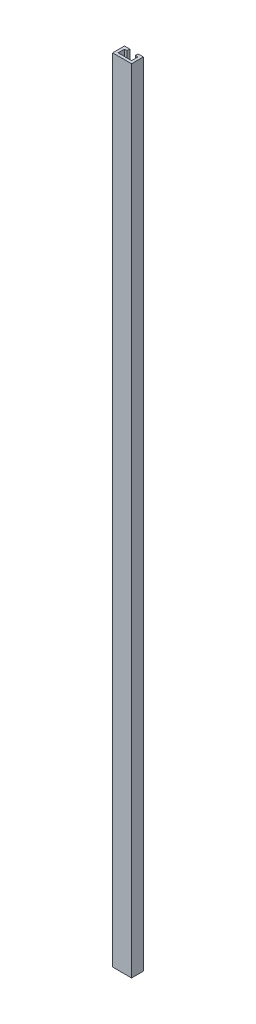
SolidWorks part; units mm, degrees
ref_plane "前视基准面" through (0, 0, 0) normal (0, 0, 1) x (1, 0, 0)
ref_plane "上视基准面" through (0, 0, 0) normal (0, 1, 0) x (1, 0, 0)
ref_plane "右视基准面" through (0, 0, 0) normal (1, 0, 0) x (0, 0, -1)
sketch "草图1" plane through (0, 0, 0) normal (0, 1, 0) x (1, 0, 0)
  line L0 (0, -5) -> (8, -5)
  line L1 (8, -5) -> (8, 0)
  line L2 (8, 0) -> (5.75, 0)
  line L3 (5.75, 0) -> (5.75, -1.15)
  line L4 (5.75, -1.15) -> (6.85, -1.15)
  line L5 (6.85, -1.15) -> (6.85, -3.85)
  line L6 (6.85, -3.85) -> (1.15, -3.85)
  line L7 (1.15, -3.85) -> (1.15, -1.15)
  line L8 (1.15, -1.15) -> (2.25, -1.15)
  line L9 (2.25, -1.15) -> (2.25, 0)
  line L10 (2.25, 0) -> (0, 0)
  line L11 (0, 0) -> (0, -5)
  line L12 (4, -3.85) -> (4, -5) construction
  line L13 (2.25, 0) -> (5.75, 0) construction
  line L14 (4, 0) -> (4, -3.85) construction
  dimension "D1" = 5
  dimension "D2" = 8
  dimension "D3" = 1.15
  dimension "D4" = 1.15
  dimension "D5" = 1.15
  dimension "D6" = 3.5
  dimension "D7" = 5.7
extrude "凸台-拉伸1" add sketch "草图1" along normal blind 335
